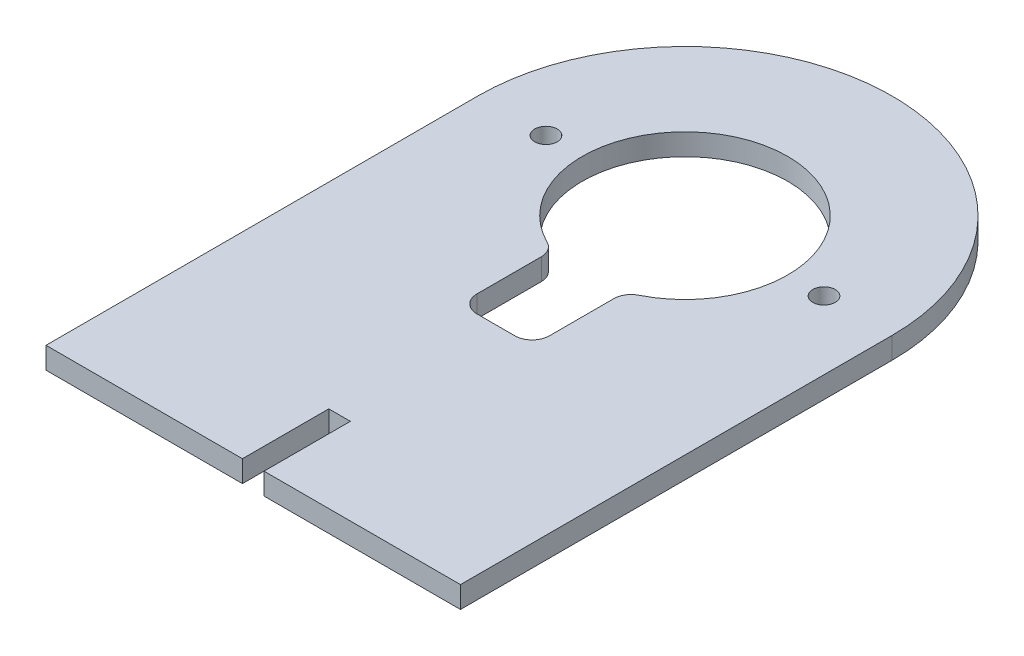
SolidWorks part; units mm, degrees
ref_plane "Front Plane" through (0, 0, 0) normal (0, 0, 1) x (1, 0, 0)
ref_plane "Top Plane" through (0, 0, 0) normal (0, 1, 0) x (1, 0, 0)
ref_plane "Right Plane" through (0, 0, 0) normal (1, 0, 0) x (0, 0, -1)
sketch "Sketch1" plane through (0, 0, 0) normal (0, 1, 0) x (1, 0, 0)
  line L0 (-20.447, 0) -> (20.447, 0) construction
  line L1 (30.48, 0) -> (30.48, -63.5)
  line L2 (-30.48, 0) -> (-30.48, -63.5)
  line L3 (-30.48, -63.5) -> (30.48, -63.5)
  line L4 (0, -63.5) -> (0, -50.8) construction
  line L5 (-1.5875, -50.8) -> (1.5875, -50.8)
  line L6 (1.5875, -50.8) -> (1.5875, -63.5)
  line L7 (-1.5875, -50.8) -> (-1.5875, -63.5)
  line L8 (0, -15.113) -> (0, -27.813) construction
  line L9 (-5.334, -27.813) -> (5.334, -27.813)
  line L10 (5.334, -27.813) -> (5.334, -14.1404)
  line L11 (-5.334, -27.813) -> (-5.334, -14.1404)
  arc A0 (30.48, 0) -> (-30.48, 0) centre (0, 0) ccw
  circle A1 centre (-20.447, 0) radius 1.651
  circle A2 centre (20.447, 0) radius 1.651
  circle A3 centre (0, 0) radius 15.113
  point P6 (0, 0)
  point P18 (0, -50.8)
  point P24 (0, -27.813)
  dimension "D1" = 60.96
  dimension "D3" = 3.302
  dimension "D4" = 3.302
  dimension "D5" = 30.226
  dimension "D2" = 40.894
  dimension "D6" = 63.5
  dimension "D7" = 12.7
  dimension "D8" = 3.175
  dimension "D9" = 12.7
  dimension "D10" = 10.668
extrude "Boss-Extrude1" add sketch "Sketch1" along normal blind 3.175 contours L1 A0 L2 L3 L7 L5 L6 A3 L10 L9 L11 A2 A1
fillet "Fillet2" radius 2.54 4 edges at (5.334, 1.5875, 27.813) (5.334, 1.5875, 14.1404) (-5.334, 1.5875, 27.813) (-5.334, 1.5875, 14.1404)
